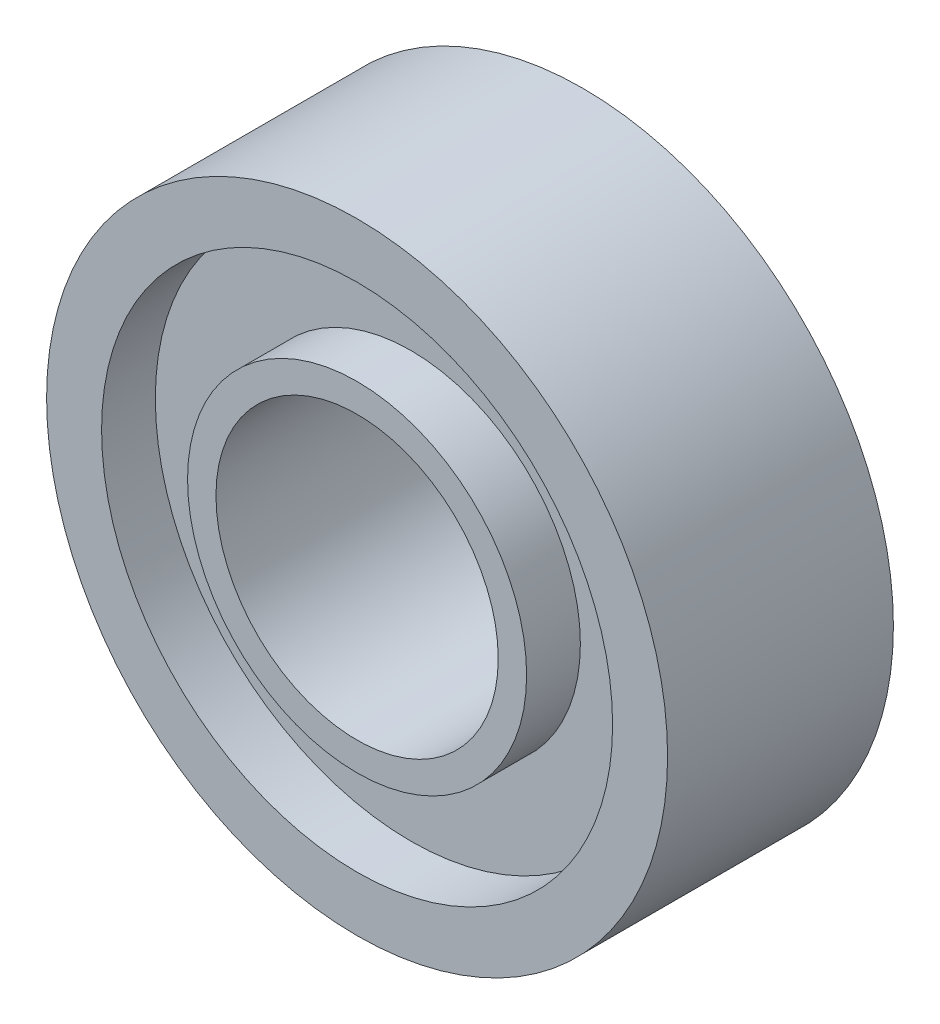
SolidWorks part; units mm, degrees
material "201 Annealed Stainless Steel (SS)"
ref_plane "Front Plane" through (0, 0, 0) normal (0, 0, 1) x (1, 0, 0)
ref_plane "Top Plane" through (0, 0, 0) normal (0, 1, 0) x (1, 0, 0)
ref_plane "Right Plane" through (0, 0, 0) normal (1, 0, 0) x (0, 0, -1)
sketch "Sketch1" plane through (0, 0, 0) normal (0, 0, 1) x (1, 0, 0)
  circle A0 centre (0, 0) radius 5.5
  circle A1 centre (0, 0) radius 2.5
  dimension "D1" = 11
  dimension "D2" = 5
extrude "Boss-Extrude1" add sketch "Sketch1" along normal blind 2
sketch "Sketch2" plane through (0, 0, 2) normal (0, 0, 1) x (1, 0, 0)
  circle A0 centre (0, 0) radius 3.003
  circle A1 centre (0, 0) radius 4.5261
extrude "Cut-Extrude1" cut sketch "Sketch2" against normal blind 0.952
mirror "Mirror1" about plane through (0, 0, 0) normal (0, 0, 1) of bodies 102
